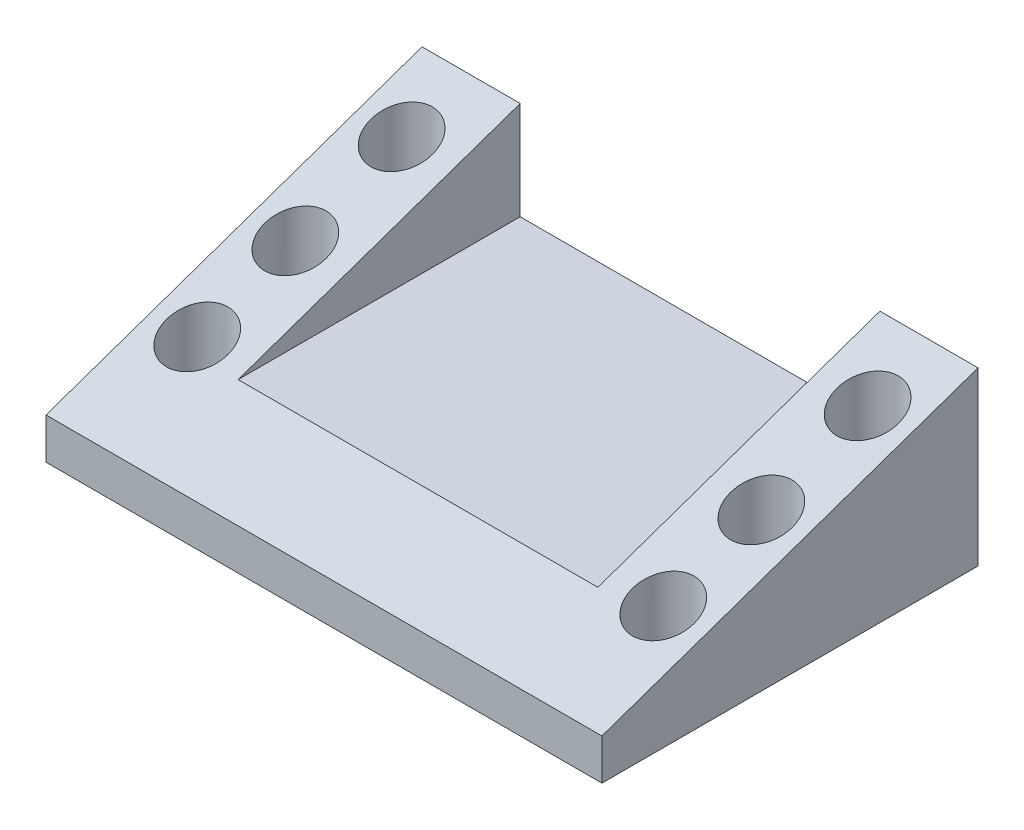
SolidWorks part; units mm, degrees
ref_plane "Front" through (0, 0, 0) normal (0, 0, 1) x (1, 0, 0)
ref_plane "Top" through (0, 0, 0) normal (0, 1, 0) x (1, 0, 0)
ref_plane "Right" through (0, 0, 0) normal (1, 0, 0) x (0, 0, -1)
sketch "Sketch1" plane through (0, 0, 0) normal (0, 1, 0) x (1, 0, 0)
  line L1 (-34, -23) -> (34, -23)
  line L2 (-34, -23) -> (-34, 23)
  line L3 (-34, 23) -> (34, 23)
  line L4 (34, -23) -> (34, 23)
  line L5 (-34, -23) -> (34, 23) construction
  line L6 (-34, 23) -> (34, -23) construction
  point P0 (0, 0)
  dimension "D1" = 68
  dimension "D2" = 46
extrude "Boss-Extrude1" add sketch "Sketch1" along normal blind 67
sketch "Sketch3" plane through (0, 67, 0) normal (0, 1, 0) x (1, 0, 0)
  line L0 (34, 23) -> (-34, 23) construction
  line L9 (-22, -23) -> (22, -23)
  line L10 (-22, -23) -> (-22, 23)
  line L13 (-22, 23) -> (22, 23)
  line L14 (22, -23) -> (22, 23)
  line L15 (-22, -23) -> (22, 23) construction
  line L16 (-22, 23) -> (22, -23) construction
  point P0 (0, 0)
  dimension "D1" = 44
extrude "Cut-Extrude2" cut sketch "Sketch3" against normal offset from surface (58 mm away) 9 up to face at (0, 0, 0)
sketch "Sketch2" plane through (34, 0, 0) normal (1, 0, 0) x (0, 0, -1)
  line L0 (-23, 5) -> (23, 21)
  line L1 (-23, 67) -> (-23, 0) construction
  line L2 (23, 67) -> (23, 0) construction
  line L3 (-23, 0) -> (23, 0) construction
  line L4 (-23, 5) -> (-23, 67)
  line L5 (-23, 67) -> (23, 67)
  line L6 (23, 67) -> (23, 21)
  dimension "D1" = 21
  dimension "D2" = 5
extrude "Cut-Extrude1" cut sketch "Sketch2" against normal up to surface (68 mm away) up to face at (-34, 33.5, 0)
sketch "Sketch4" plane through (0, 0, 0) normal (0, -1, 0) x (-1, 0, 0)
  line L0 (-28.5, 15) -> (-34, 15) construction
  line L1 (-34, -23) -> (-34, 23) construction
  line L2 (28.5, 15) -> (34, 15) construction
  line L3 (34, 23) -> (34, -23) construction
  line L4 (-28.5, 15) -> (-28.5, 2) construction
  line L5 (-28.5, 2) -> (-28.5, -10) construction
  line L6 (28.5, 15) -> (28.5, 2) construction
  line L7 (28.5, 2) -> (28.5, -10) construction
  line L9 (28.5, -10) -> (28.5, -13.75) construction
  line L10 (34, -23) -> (-34, -23) construction
  circle A0 centre (-28.5, 15) radius 3.75
  circle A1 centre (-28.5, 2) radius 3.75
  circle A2 centre (-28.5, -10) radius 3.75
  circle A3 centre (28.5, 15) radius 3.75
  circle A4 centre (28.5, 2) radius 3.75
  circle A5 centre (28.5, -10) radius 3.75
  point P20 (0, 0)
  dimension "D1" = 7.5
  dimension "D5" = 5.5
  dimension "D2" = 9.25
  dimension "D3" = 12
  dimension "D4" = 13
extrude "Cut-Extrude3" cut sketch "Sketch4" against normal up to surface (19.5217 mm away)
